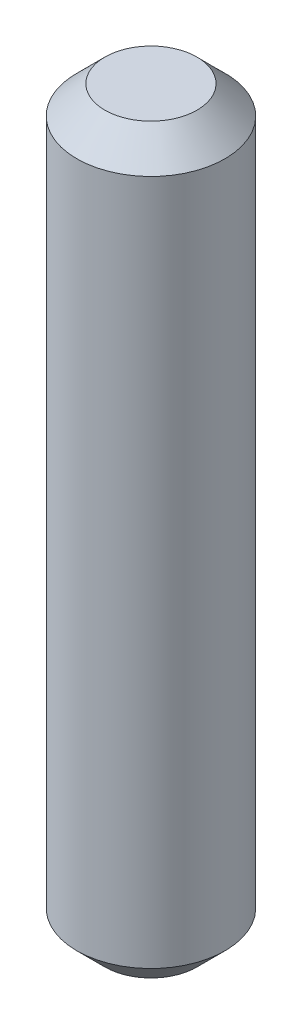
SolidWorks part; units mm, degrees
ref_plane "Front Plane" through (0, 0, 0) normal (0, 0, 1) x (1, 0, 0)
ref_plane "Top Plane" through (0, 0, 0) normal (0, 1, 0) x (1, 0, 0)
ref_plane "Right Plane" through (0, 0, 0) normal (1, 0, 0) x (0, 0, -1)
sketch "Sketch1" plane through (0, 0, 0) normal (0, 1, 0) x (1, 0, 0)
  circle A0 centre (0, 0) radius 1.585
  dimension "D1" = 3.17
extrude "Boss-Extrude1" add sketch "Sketch1" along normal blind 15.87
chamfer "Chamfer1" distance 0.6 angle 45 1 edges at (0, 15.87, 1.585)
chamfer "Chamfer2" distance 0.6 angle 45 1 edges at (0, 0, 1.585)
